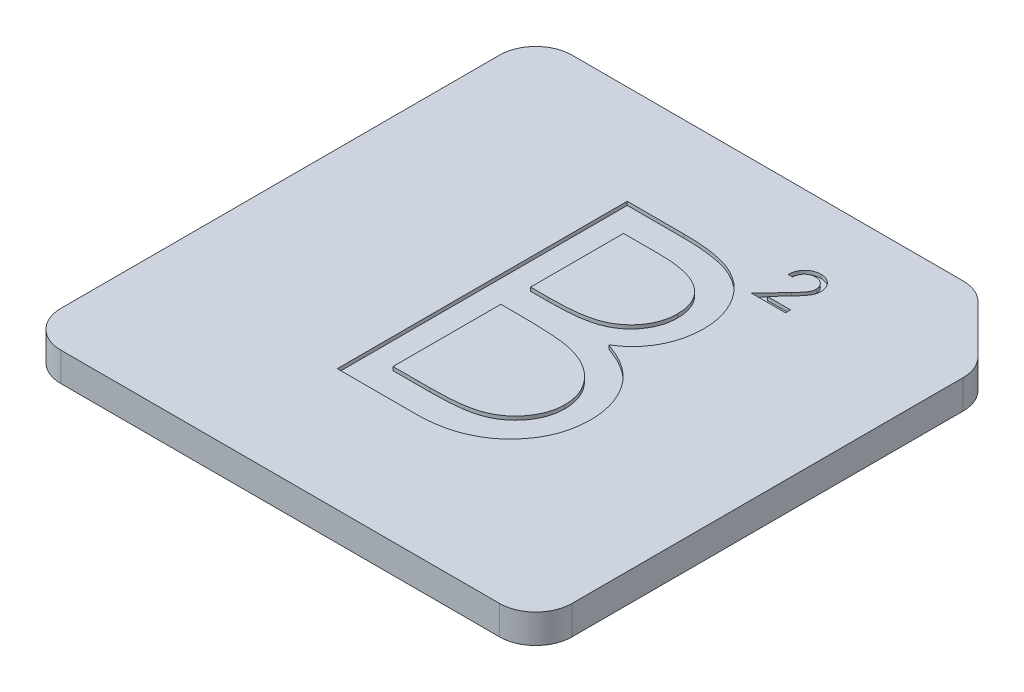
SolidWorks part; units mm, degrees
ref_plane "Front Plane" through (0, 0, 0) normal (0, 0, 1) x (1, 0, 0)
ref_plane "Top Plane" through (0, 0, 0) normal (0, 1, 0) x (1, 0, 0)
ref_plane "Right Plane" through (0, 0, 0) normal (1, 0, 0) x (0, 0, -1)
sketch "Sketch1" plane through (0, 0, 0) normal (0, 1, 0) x (1, 0, 0)
  line L0 (25.75, 35.25) -> (35.25, 25.75)
  line L1 (-35.25, 35.25) -> (25.75, 35.25)
  line L2 (-35.25, 35.25) -> (-35.25, -35.25)
  line L3 (-35.25, -35.25) -> (35.25, -35.25)
  line L4 (35.25, 25.75) -> (35.25, -35.25)
extrude "Boss-Extrude1" add sketch "Sketch1" along normal blind 4
fillet "Fillet1" radius 5 1 edges at (-35.25, 2, 35.25)
fillet "Fillet5" radius 5 1 edges at (35.25, 2, 35.25)
fillet "Fillet6" radius 5 1 edges at (-35.25, 2, -35.25)
fillet "Fillet7" radius 5 2 edges at (35.25, 2, -25.75) (25.75, 2, -35.25)
sketch "Sketch3" plane through (0, 4, 0) normal (0, 1, 0) x (1, 0, 0)
  text T0 "B" font "Century Gothic" height 40
extrude "Cut-Extrude1" cut sketch "Sketch3" against normal blind 0.5
sketch "Sketch4" plane through (0, 4, 0) normal (0, 1, 0) x (1, 0, 0)
  text T0 "2" font "Century Gothic" height in points 26
extrude "Cut-Extrude2" cut sketch "Sketch4" against normal blind 0.5
sketch "Sketch5" plane through (0, 0, 0) normal (0, -1, 0) x (1, 0, 0)
  circle A0 centre (-30.5, -30.5) radius 3.25
  circle A1 centre (-30.5, 30.5) radius 3.25
  circle A2 centre (30.5, 30.5) radius 3.25
extrude "Cut-Extrude3" cut sketch "Sketch5" against normal blind 2.5
